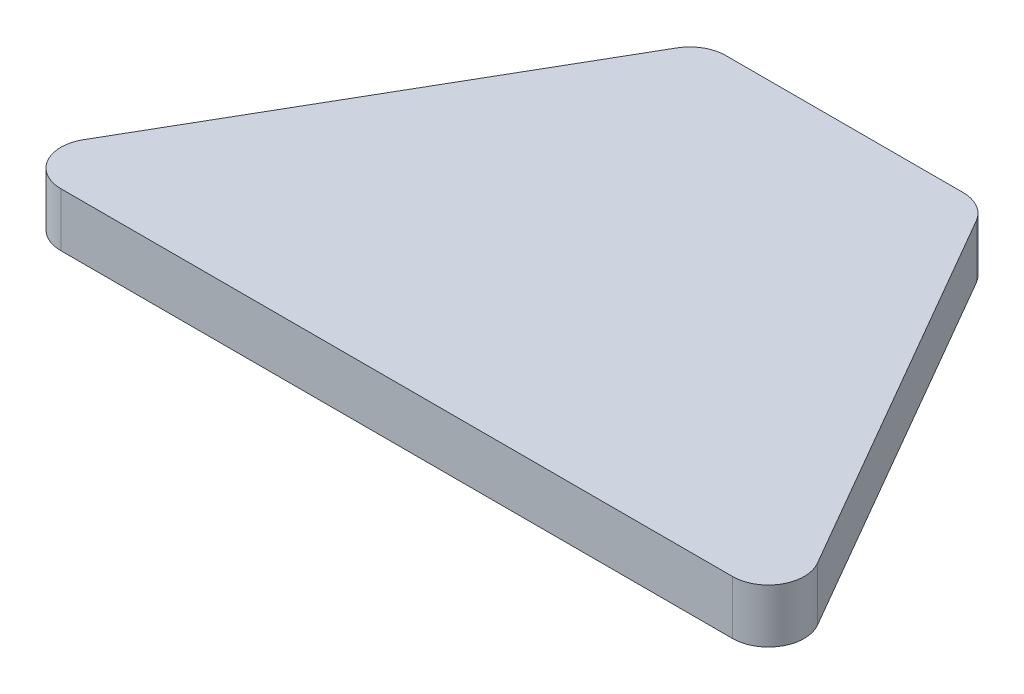
SolidWorks part; units mm, degrees
material "99.5% Aluminum Oxide"
ref_plane "Front Plane" through (0, 0, 0) normal (0, 0, 1) x (1, 0, 0)
ref_plane "Top Plane" through (0, 0, 0) normal (0, 1, 0) x (1, 0, 0)
ref_plane "Right Plane" through (0, 0, 0) normal (1, 0, 0) x (0, 0, -1)
sketch "Sketch1" plane through (0, 0, 0) normal (0, 1, 0) x (1, 0, 0)
  line L1 (-14.2978, -12.5) -> (14.2978, -12.5)
  line L2 (-14.2978, -12.5) -> (-14.2978, 12.5) construction
  line L3 (-14.2978, 12.5) -> (14.2978, 12.5) construction
  line L4 (14.2978, -12.5) -> (14.2978, 12.5) construction
  line L5 (-14.2978, -12.5) -> (14.2978, 12.5) construction
  line L6 (-14.2978, 12.5) -> (14.2978, -12.5) construction
  line L8 (-7.7831, 12.5) -> (7.7831, 12.5)
  line L11 (0, 11.2271) -> (0, -49988.7729) construction
  line L14 (-7.7831, 12.5) -> (-22.2169, -12.5)
  line L15 (-22.2169, -12.5) -> (-14.2978, -12.5)
  line L16 (7.7831, 12.5) -> (22.2169, -12.5)
  line L17 (22.2169, -12.5) -> (14.2978, -12.5)
  line L24 (15, 0) -> (-15, 0) construction
  point P0 (0, 0)
  point P14 (0, 12.5)
  dimension "D1" = 25
  dimension "D2" = 30
  dimension "D4" = 60
extrude "Boss-Extrude1" add sketch "Sketch1" along normal mid plane 3
fillet "Fillet5" radius 2 4 edges at (22.2169, 0, 12.5) (-22.2169, 0, 12.5) (-7.7831, 0, -12.5) (7.7831, 0, -12.5)
equation "\"panel_width\"= 5.5in"
equation "\"finger_joint_width\"= 30mm"
